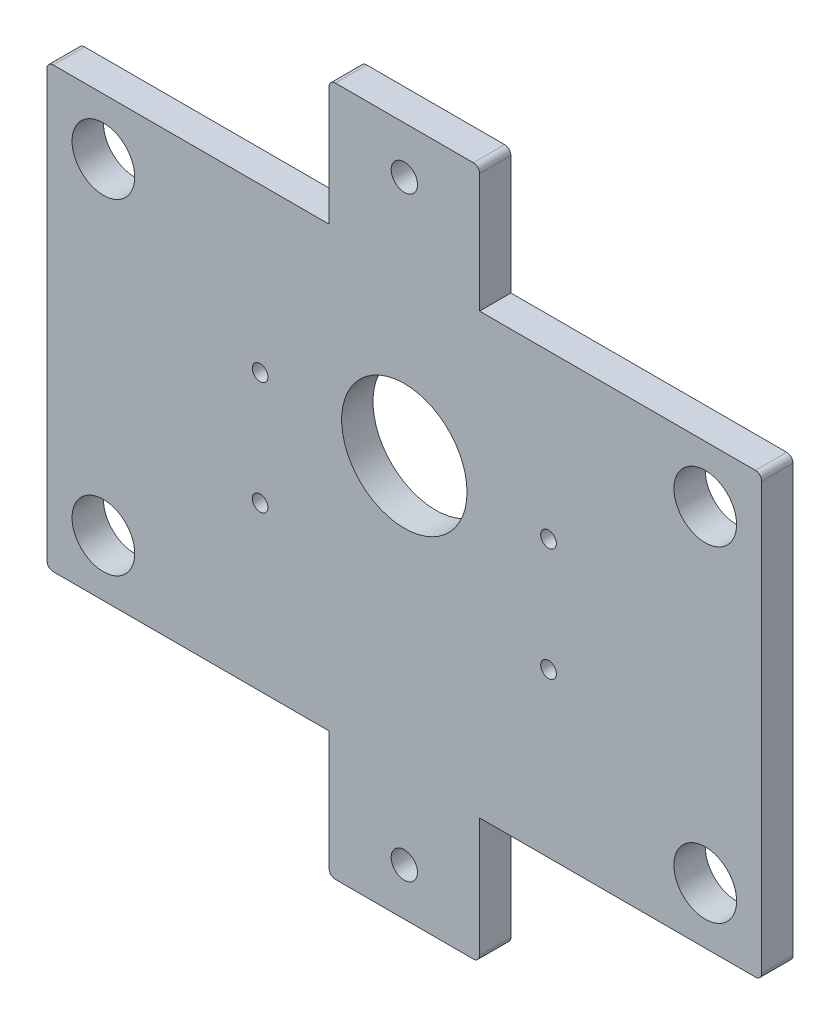
SolidWorks part; units mm, degrees
ref_plane "前视基准面" through (0, 0, 0) normal (0, 0, 1) x (1, 0, 0)
ref_plane "上视基准面" through (0, 0, 0) normal (0, 1, 0) x (1, 0, 0)
ref_plane "右视基准面" through (0, 0, 0) normal (1, 0, 0) x (0, 0, -1)
sketch "草图1" plane through (0, 0, 0) normal (0, 0, 1) x (1, 0, 0)
  line L0 (-57, 35) -> (-57, -35)
  line L1 (-57, -35) -> (-12, -35)
  line L2 (-12, -35) -> (-12, -55)
  line L3 (-12, -55) -> (12, -55)
  line L4 (12, -55) -> (12, -35)
  line L5 (12, -35) -> (57, -35)
  line L6 (57, -35) -> (57, 35)
  line L7 (57, 35) -> (12, 35)
  line L8 (12, 35) -> (12, 55)
  line L9 (12, 55) -> (-12, 55)
  line L10 (-12, 55) -> (-12, 35)
  line L11 (-12, 35) -> (-57, 35)
  line L12 (0, -1000) -> (0, 49000) construction
  line L13 (-1000, 0) -> (49000, 0) construction
  dimension "D1" = 24
  dimension "D2" = 20
  dimension "D3" = 45
  dimension "D4" = 45
  dimension "D5" = 70
  dimension "D6" = 70
  dimension "D7" = 20
  dimension "D8" = 20
  dimension "D9" = 45
  dimension "D10" = 12
  dimension "D11" = 24
  dimension "D12" = 35
extrude "凸台-拉伸1" add sketch "草图1" along normal blind 5
fillet "圆角2" radius 1 8 edges at (12, 55, 2.5) (-12, 55, 2.5) (12, -55, 2.5) (-12, -55, 2.5) (-57, 35, 2.5) (-57, -35, 2.5) (57, -35, 2.5) (57, 35, 2.5)
sketch "草图3" plane through (0, 0, 5) normal (0, 0, 1) x (1, 0, 0)
  line L0 (0, -1000) -> (0, 49000) construction
  line L1 (-12, 35) -> (-56, 35) construction
  line L2 (11, 55) -> (-11, 55) construction
  circle A0 centre (-23, 9) radius 2 construction
  circle A1 centre (-23, -9) radius 2 construction
  circle A2 centre (0, 47.5) radius 2 construction
  dimension "D1" = 23
  dimension "D2" = 18
  dimension "D4" = 7.5
  dimension "D3" = 26
hole_wizard "M3 螺纹孔的螺纹孔钻头1" positions "3D草图1" profile "草图4" hole size "M3" standard "GB" end condition through all
sketch3d "3D草图1"
  point P0 (-23, 9, 5)
  point P3 (-23, -9, 5)
sketch "草图4" plane through (-23, 9, 5) normal (1, 0, 0) x (0, -1, 0)
  line L0 (0, 0) -> (0, 5)
  line L1 (0, 5) -> (1.25, 5)
  line L2 (1.25, 5) -> (1.25, 0)
  line L5 (1.25, 0) -> (0, 0)
  line L11 (0, -6.35) -> (0, 107.95) construction
  dimension "通孔孔直径" = 2.5
  dimension "通孔孔深度" = 5
mirror "镜向1" about plane through (0, 0, 0) normal (1, 0, 0) of "M3 螺纹孔的螺纹孔钻头1"
sketch "草图5" plane through (0, 0, 5) normal (0, 0, 1) x (1, 0, 0)
  line L0 (-57, 34) -> (-57, -34) construction
  line L2 (-12, 35) -> (-56, 35) construction
  circle A0 centre (-48, 26) radius 5
  circle A1 centre (-48, -26) radius 5
  dimension "D1" = 9
  dimension "D3" = 9
  dimension "D2" = 9
  dimension "D4" = 52
extrude "切除-拉伸1" cut sketch "草图5" against normal blind 5
mirror "镜向2" about plane through (0, 0, 0) normal (1, 0, 0) of "切除-拉伸1"
hole_wizard "M5 螺纹孔的螺纹孔钻头1" positions "3D草图3" profile "草图6" hole size "M5" standard "GB" end condition through all
sketch3d "3D草图3"
  point P0 (0, 47.5, 5)
sketch "草图6" plane through (0, 47.5, 5) normal (1, 0, 0) x (0, -1, 0)
  line L0 (0, 0) -> (0, 5)
  line L1 (0, 5) -> (2.1, 5)
  line L2 (2.1, 5) -> (2.1, 0)
  line L5 (2.1, 0) -> (0, 0)
  line L11 (0, -6.35) -> (0, 107.95) construction
  dimension "通孔孔直径" = 4.2
  dimension "通孔孔深度" = 5
mirror "镜向3" about plane through (0, 0, 0) normal (0, 1, 0) of "M5 螺纹孔的螺纹孔钻头1"
sketch "草图7" plane through (0, 0, 5) normal (0, 0, 1) x (1, 0, 0)
  line L1 (0, -201000) -> (0, 249000) construction
  line L2 (11, 55) -> (-11, 55) construction
  circle A0 centre (0, 9) radius 10
  dimension "D1" = 46
extrude "切除-拉伸2" cut sketch "草图7" against normal through all
